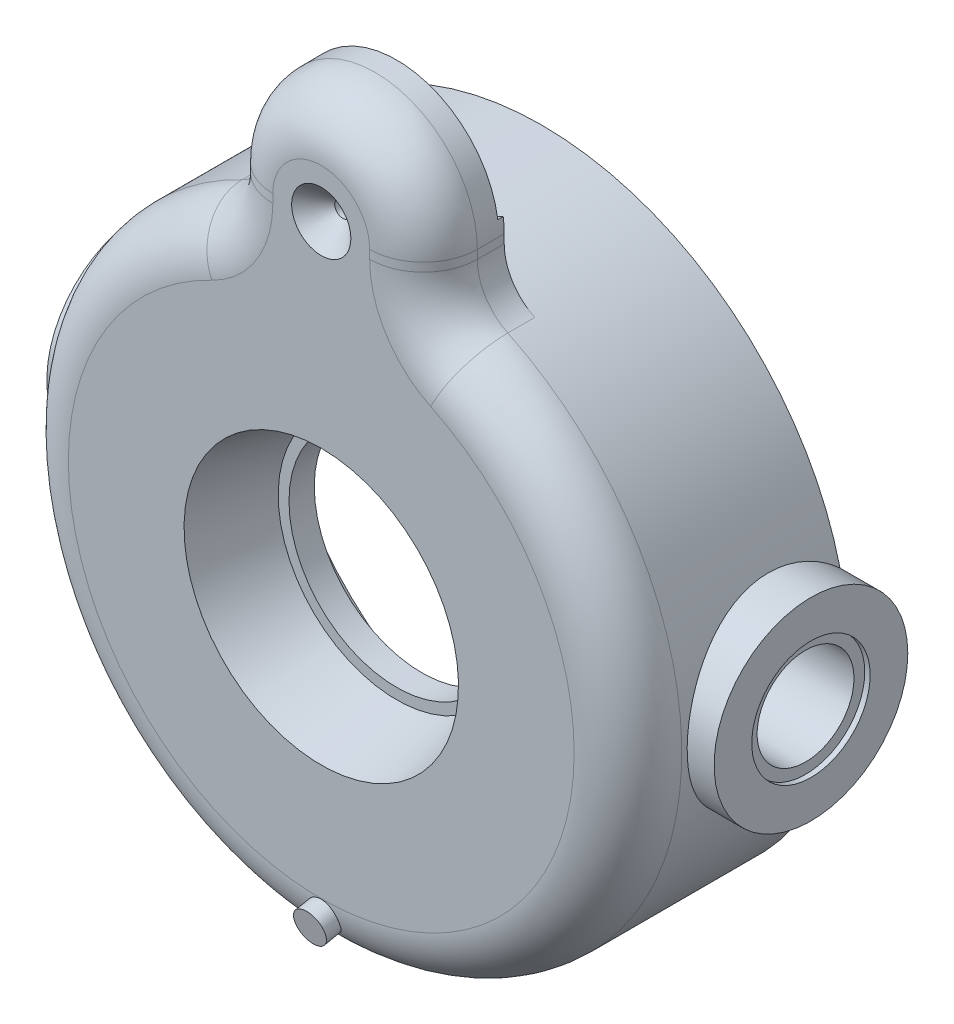
SolidWorks part; units mm, degrees
ref_plane "前视基准面" through (0, 0, 0) normal (0, 0, 1) x (1, 0, 0)
ref_plane "上视基准面" through (0, 0, 0) normal (0, 1, 0) x (1, 0, 0)
ref_plane "右视基准面" through (0, 0, 0) normal (1, 0, 0) x (0, 0, -1)
sketch "草图1" plane through (0, 0, 0) normal (0, 0, 1) x (1, 0, 0)
  circle A0 centre (0, 0) radius 57
  dimension "D1" = 114
extrude "凸台-拉伸1" add sketch "草图1" along normal blind 41
sketch "草图4" plane through (0, 0, 41) normal (0, 0, 1) x (1, 0, 0)
  line L0 (0, -22.55) -> (0, 22.55) construction
  line L1 (19, 62) -> (19, 60.3987)
  line L2 (-19, 62) -> (-19, 60.3987)
  arc A0 (19, 62) -> (-19, 62) centre (0, 62) ccw
  circle A1 centre (0, 0) radius 57 construction
  arc A2 (19, 60.3987) -> (24.6716, 51.3839) centre (29, 60.3987) ccw
  circle A3 centre (0, 0) radius 57
  arc A4 (-24.6716, 51.3839) -> (24.6716, 51.3839) centre (0, 0) ccw
  arc A5 (-19, 60.3987) -> (-24.6716, 51.3839) centre (-29, 60.3987) cw
  point P11 (19, 53.7401)
  point P16 (-19, 53.7401)
  dimension "D1" = 38
  dimension "D4" = 10
  dimension "D2" = 0
  dimension "D3" = 62
extrude "凸台-拉伸3" add sketch "草图4" against normal blind 15
sketch "草图5" plane through (0, 0, 26) normal (0, 0, 1) x (1, 0, 0)
  line L0 (0, -22.55) -> (0, 22.55) construction
  line L1 (0, 60) -> (36.2544, 60) construction
  line L2 (0, 81) -> (20.771, 81) construction
  circle A0 centre (0, 100) radius 40
  arc A2 (19, 62) -> (-19, 62) centre (0, 62) ccw construction
  dimension "D1" = 80
  dimension "D2" = 21
extrude "切除-拉伸1" cut sketch "草图5" along normal blind 1
sketch "草图6" plane through (0, 0, 0) normal (0, 0, -1) x (-1, 0, 0)
  circle A0 centre (0, 0) radius 51
  dimension "D1" = 102
ref_plane "基准面1" through (0, 0, 22.3) normal (0, 0, -1) x (-1, 0, 0)
sketch "草图7" plane through (0, 0, 22.3) normal (0, 0, -1) x (-1, 0, 0)
  circle A0 centre (0, 0) radius 45
  dimension "D1" = 90
loft "切除-放样1" cut profiles "草图6", "草图7"
sketch "草图8" plane through (0, 0, 22.3) normal (0, 0, -1) x (-1, 0, 0)
  circle A0 centre (0, 0) radius 20
  dimension "D1" = 40
extrude "切除-拉伸2" cut sketch "草图8" against normal through all
sketch "草图10" plane through (0, 0, 0) normal (1, 0, 0) x (0, 0, -1)
  line L0 (0, 0) -> (-69.5565, 0) construction
  line L1 (-41, 0) -> (-41, 25.5)
  line L2 (-41, 51.3839) -> (-41, -57) construction
  line L3 (-41, 25.5) -> (-27, 22)
  line L4 (-27, 22) -> (-27, 0)
  line L5 (-41, 0) -> (-27, 0)
  dimension "D1" = 14
  dimension "D2" = 51
  dimension "D3" = 44
revolve "切除-旋转1" cut sketch "草图10" angle 360 about L0
sketch "草图11" plane through (0, 0, 41) normal (0, 0, 1) x (1, 0, 0)
  point P0 (0, 62)
hole_wizard "Ø3.0mm 暗销孔1" positions "草图11" profile "草图12" hole size "Ø3.0" standard "GB"
sketch "草图12" plane through (0, 62, 41) normal (1, 0, 0) x (0, -1, 0)
  line L0 (0, 0) -> (0, 7.9013)
  line L1 (0, 7.9013) -> (1.5, 7)
  line L2 (1.5, 7) -> (1.5, 4)
  line L3 (1.5, 4) -> (5.5, 0)
  line L5 (5.5, 0) -> (0, 0)
  line L6 (-1.5, 4) -> (-5.5, 0) construction
  line L10 (0, 7.9013) -> (-1.5, 7) construction
  line L11 (0, -6.35) -> (0, 107.95) construction
  dimension "孔直径" = 3
  dimension "孔深度" = 7
  dimension "近端锥形沉头孔直径" = 11
  dimension "近端锥形沉头孔角度" = 90
  dimension "导头角度" = 118
fillet "圆角2" radius 10 6 edges at (-20.5359, 55.0734, 41) (-19, 61.1993, 41) (0, 81, 41) (19, 61.1993, 41) (20.5359, 55.0734, 41) (0, -57, 41)
sketch "草图14" plane through (0, 0, 0) normal (1, 0, 0) x (0, 0, -1)
  line L0 (22.55, 0) -> (-22.55, 0) construction
  line L1 (-41, 42.3692) -> (-41, -47) construction
  circle A0 centre (-12, 0) radius 18
  dimension "D1" = 36
  dimension "D2" = 29
extrude "凸台-拉伸4" add sketch "草图14" against normal blind 17 from offset 62
sketch "草图15" plane through (62, 0, 0) normal (1, 0, 0) x (0, 0, -1)
  circle A0 centre (-12, 0) radius 11
  dimension "D1" = 22
extrude "切除-拉伸3" cut sketch "草图15" against normal blind 1
sketch "草图16" plane through (61, 0, 0) normal (1, 0, 0) x (0, 0, -1)
  circle A0 centre (-12, 0) radius 9
  dimension "D1" = 18
extrude "切除-拉伸4" cut sketch "草图16" against normal up to next
mirror "镜向2" about plane through (0, 0, 0) normal (1, 0, 0) of "切除-拉伸3", "凸台-拉伸4", "切除-拉伸4"
sketch "草图17" plane through (0, 0, 0) normal (1, 0, 0) x (0, 0, -1)
  line L0 (-43.1, -50.6) -> (-35.0547, -48.8899)
  line L1 (-41, 42.3692) -> (-41, -47) construction
  line L2 (-31, -57) -> (0, -57) construction
  point P4 (-46.5202, -56.817)
  point P7 (-35.0547, -48.8899)
  point P8 (0, 0)
  dimension "D1" = 78
  dimension "D2" = 2.1
  dimension "D3" = 6.4
sweep "扫描1" add path "草图17" circular profile diameter 6 parameters "D3"=6
